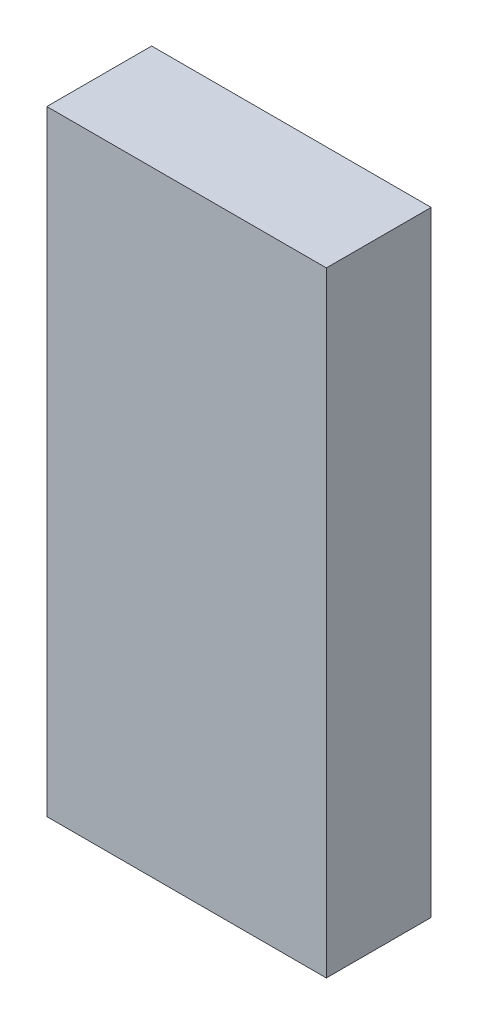
SolidWorks part; units mm, degrees
material "Резина"
ref_plane "Спереди" through (0, 0, 0) normal (0, 0, 1) x (1, 0, 0)
ref_plane "Сверху" through (0, 0, 0) normal (0, 1, 0) x (1, 0, 0)
ref_plane "Справа" through (0, 0, 0) normal (1, 0, 0) x (0, 0, -1)
sketch "Эскиз1" plane through (0, 0, 0) normal (0, 0, 1) x (1, 0, 0)
  line L1 (-0.5836, 4.7738) -> (3.4164, 4.7738)
  line L2 (-0.5836, 4.7738) -> (-0.5836, -4.0262)
  line L3 (-0.5836, -4.0262) -> (3.4164, -4.0262)
  line L4 (3.4164, 4.7738) -> (3.4164, -4.0262)
  dimension "D1" = 8.8
  dimension "D2" = 4
extrude "Бобышка-Вытянуть1" add sketch "Эскиз1" along normal blind 1.5
